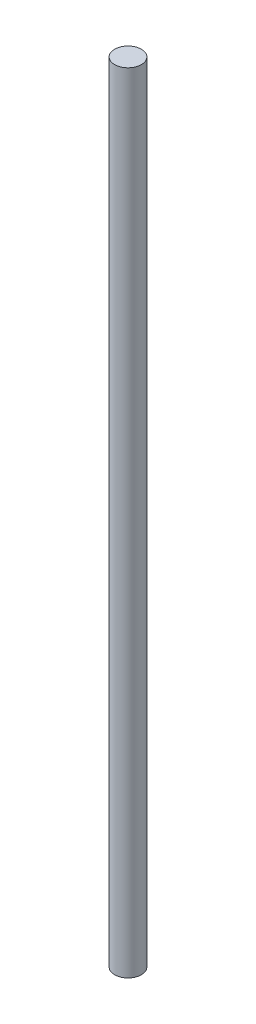
SolidWorks part; units mm, degrees
ref_plane "Front Plane" through (0, 0, 0) normal (0, 0, 1) x (1, 0, 0)
ref_plane "Top Plane" through (0, 0, 0) normal (0, 1, 0) x (1, 0, 0)
ref_plane "Right Plane" through (0, 0, 0) normal (1, 0, 0) x (0, 0, -1)
sketch "Sketch3" plane through (0, 0, 0) normal (0, 1, 0) x (1, 0, 0)
  circle A0 centre (0, 0) radius 25.4
extrude "Boss-Extrude3" add sketch "Sketch3" along normal blind 1500
